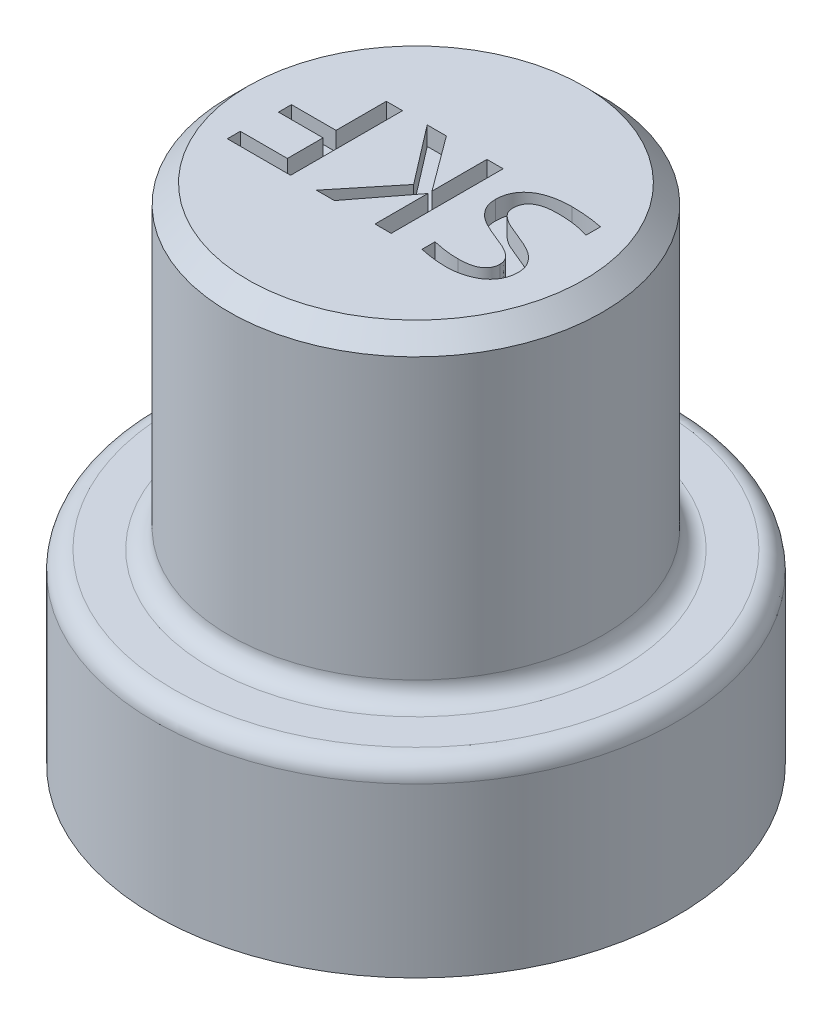
SolidWorks part; units mm, degrees
ref_plane "Front Plane" through (0, 0, 0) normal (1, 0, 0) x (0, 1, 0)
ref_plane "Top Plane" through (0, 0, 0) normal (0, 0, 1) x (0, 1, 0)
ref_plane "Right Plane" through (0, 0, 0) normal (0, 1, 0) x (-1, 0, 0)
sketch "Sketch1" plane through (0, 0, 0) normal (0, 0, 1) x (0, 1, 0)
  line L0 (0, 14) -> (10, 14)
  line L1 (10, 14) -> (10, 10)
  line L2 (10, 10) -> (27, 10)
  line L3 (27, 10) -> (27, 0)
  line L4 (27, 0) -> (0, 0)
  line L5 (0, 0) -> (0, 14)
  point P2 (0, 0)
  dimension "D1" = 10
  dimension "D2" = 17
  dimension "D3" = 10
  dimension "D4" = 14
revolve "Revolve1" add sketch "Sketch1" angle 360 about L4
chamfer "Chamfer1" distance 1 angle 45 1 edges at (-10, 27, 0)
fillet "Fillet1" radius 1 1 edges at (-10, 10, 0)
fillet "Fillet2" radius 1 1 edges at (-14, 10, 0)
sketch "Sketch2" plane through (0, 27, 0) normal (0, 1, 0) x (-1, 0, 0)
  line L0 (-7.5, -3) -> (7.5, -3) construction
  text T0 "SKF" font "Consolas" height 6
  point P2 (0, -3)
  dimension "D1" = 3
  dimension "D2" = 15
extrude "Cut-Extrude1" cut sketch "Sketch2" against normal blind 1
